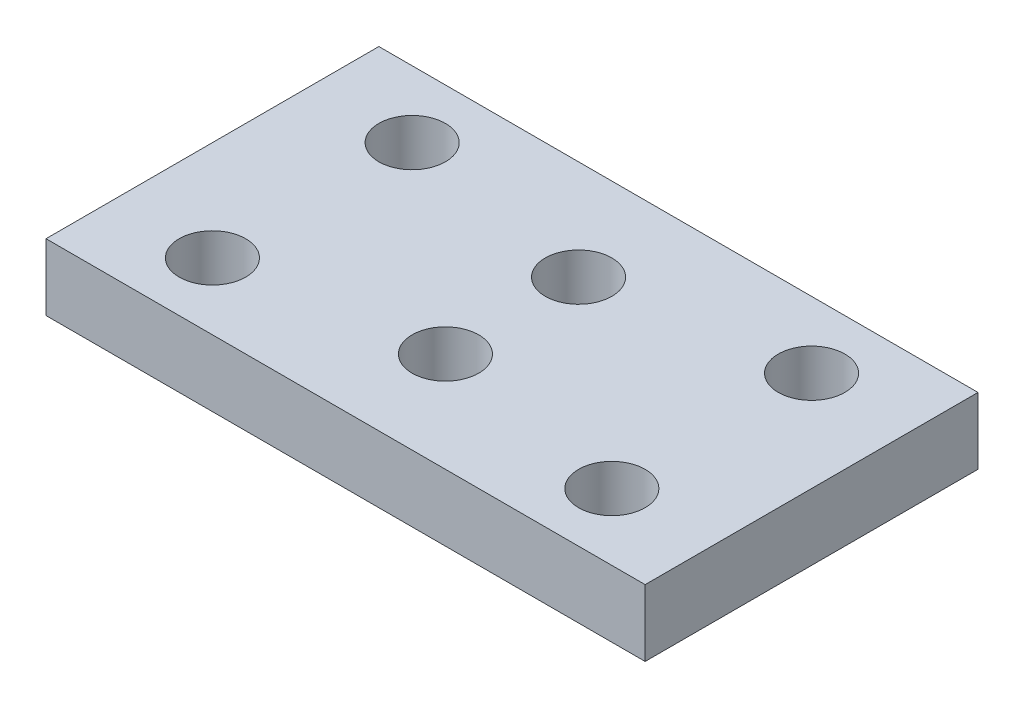
SolidWorks part; units mm, degrees
material "6061 Alloy"
ref_plane "Front Plane" through (0, 0, 0) normal (0, 0, 1) x (1, 0, 0)
ref_plane "Top Plane" through (0, 0, 0) normal (0, 1, 0) x (1, 0, 0)
ref_plane "Right Plane" through (0, 0, 0) normal (1, 0, 0) x (0, 0, -1)
sketch "Sketch1" plane through (0, 0, 0) normal (0, 1, 0) x (1, 0, 0)
  line L0 (9.525, 25.4) -> (9.525, 6.35) construction
  line L1 (0, 0) -> (57.15, 0)
  line L2 (0, 0) -> (0, 31.75)
  line L3 (0, 31.75) -> (57.15, 31.75)
  line L4 (57.15, 0) -> (57.15, 31.75)
  line L5 (28.575, 0) -> (28.575, 9.525) construction
  line L6 (9.525, 15.875) -> (0, 15.875) construction
  line L7 (47.625, 25.4) -> (47.625, 6.35) construction
  line L8 (47.625, 15.875) -> (57.15, 15.875) construction
  line L9 (28.575, 9.525) -> (28.575, 22.225) construction
  line L10 (28.575, 22.225) -> (28.575, 31.75) construction
  circle A0 centre (9.525, 25.4) radius 3.175
  circle A1 centre (47.625, 25.4) radius 3.175
  circle A2 centre (47.625, 6.35) radius 3.175
  circle A3 centre (9.525, 6.35) radius 3.175
  circle A4 centre (28.575, 22.225) radius 3.175
  circle A5 centre (28.575, 9.525) radius 3.175
  dimension "D3" = 6.35
  dimension "D1" = 31.75
  dimension "D2" = 57.15
  dimension "D4" = 38.1
  dimension "D5" = 19.05
  dimension "D6" = 12.7
extrude "Boss-Extrude1" add sketch "Sketch1" along normal blind 6.35
